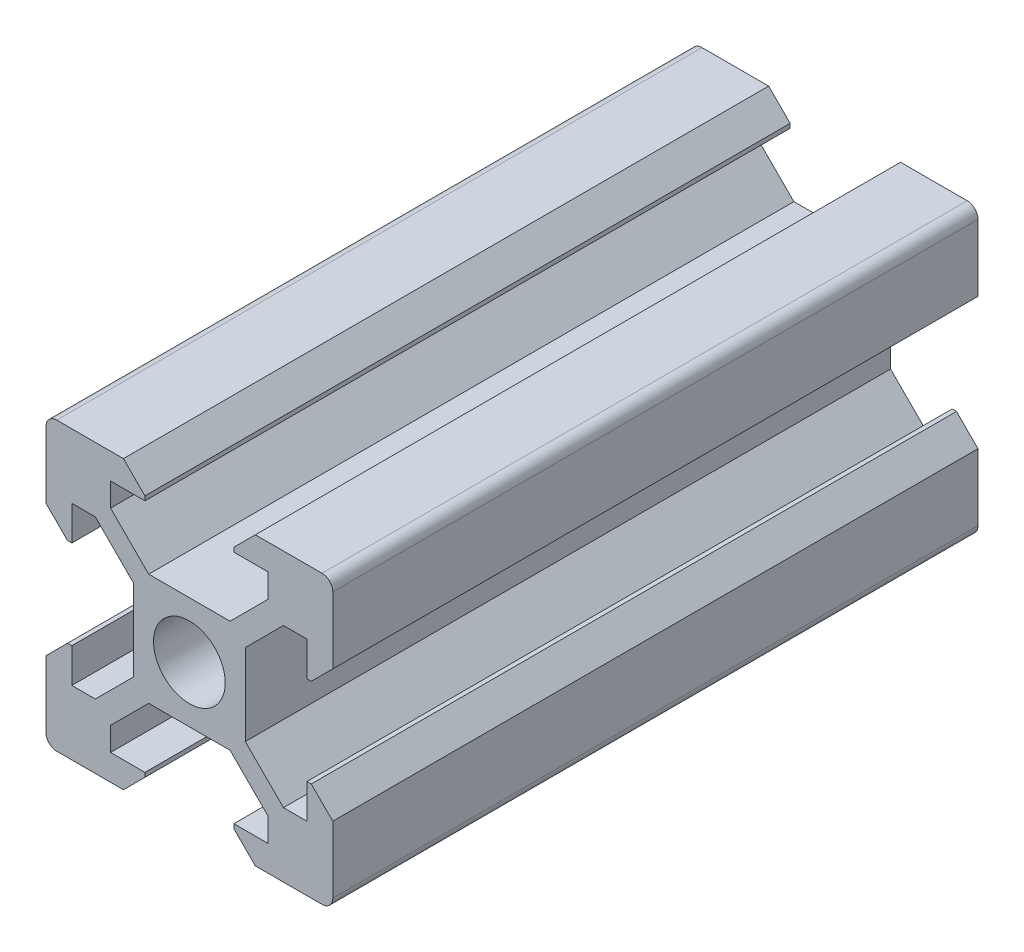
SolidWorks part; units mm, degrees
other "Markup1"
sketch "Sketch1" plane through (10, 10, 480) normal (0.5774, 0.5773, 0.5774) x (0.7071, 0, -0.7071)
ref_plane "Alzado" through (0, 0, 0) normal (0, 0, 1) x (1, 0, 0)
ref_plane "Planta" through (0, 0, 0) normal (0, 1, 0) x (1, 0, 0)
ref_plane "Vista lateral" through (0, 0, 0) normal (1, 0, 0) x (0, 0, -1)
sketch "Croquis1" plane through (0, 0, 0) normal (0, 0, 1) x (1, 0, 0)
  line L0 (-4.6, 10) -> (-3.1, 8.5)
  line L3 (-4.6, 10) -> (-9.25, 10)
  line L5 (-3.1, 8.5) -> (-3.1, 8.2)
  line L6 (-3.1, 8.2) -> (-5.5, 8.2)
  line L7 (-5.5, 8.2) -> (-5.5, 6.5607)
  line L8 (-5.5, 6.5607) -> (-2.84, 3.9007)
  line L9 (-2.84, 3.9007) -> (0, 3.9007)
  line L10 (0, 0) -> (-15.3499, 15.3499) construction
  line L11 (-3.9007, 2.84) -> (-3.9007, 0)
  line L12 (-6.5607, 5.5) -> (-3.9007, 2.84)
  line L13 (-8.2, 5.5) -> (-6.5607, 5.5)
  line L14 (-8.2, 3.1) -> (-8.2, 5.5)
  line L15 (-8.5, 3.1) -> (-8.2, 3.1)
  line L16 (-10, 4.6) -> (-10, 9.25)
  line L17 (-10, 4.6) -> (-8.5, 3.1)
  line L18 (10, 4.6) -> (8.5, 3.1)
  line L19 (10, 4.6) -> (10, 9.25)
  line L20 (8.5, 3.1) -> (8.2, 3.1)
  line L21 (8.2, 3.1) -> (8.2, 5.5)
  line L22 (8.2, 5.5) -> (6.5607, 5.5)
  line L23 (6.5607, 5.5) -> (3.9007, 2.84)
  line L24 (3.9007, 2.84) -> (3.9007, 0)
  line L25 (5.5, 6.5607) -> (2.84, 3.9007)
  line L26 (5.5, 8.2) -> (5.5, 6.5607)
  line L27 (3.1, 8.2) -> (5.5, 8.2)
  line L28 (3.1, 8.5) -> (3.1, 8.2)
  line L29 (4.6, 10) -> (9.25, 10)
  line L30 (4.6, 10) -> (3.1, 8.5)
  line L31 (2.84, 3.9007) -> (0, 3.9007)
  line L32 (4.6, -10) -> (3.1, -8.5)
  line L33 (4.6, -10) -> (9.25, -10)
  line L34 (3.1, -8.5) -> (3.1, -8.2)
  line L35 (3.1, -8.2) -> (5.5, -8.2)
  line L36 (5.5, -8.2) -> (5.5, -6.5607)
  line L37 (5.5, -6.5607) -> (2.84, -3.9007)
  line L38 (2.84, -3.9007) -> (0, -3.9007)
  line L39 (6.5607, -5.5) -> (3.9007, -2.84)
  line L40 (8.2, -5.5) -> (6.5607, -5.5)
  line L41 (8.2, -3.1) -> (8.2, -5.5)
  line L42 (8.5, -3.1) -> (8.2, -3.1)
  line L43 (10, -4.6) -> (10, -9.25)
  line L44 (10, -4.6) -> (8.5, -3.1)
  line L45 (3.9007, -2.84) -> (3.9007, 0)
  line L46 (-10, -4.6) -> (-8.5, -3.1)
  line L47 (-10, -4.6) -> (-10, -9.25)
  line L48 (-8.5, -3.1) -> (-8.2, -3.1)
  line L49 (-8.2, -3.1) -> (-8.2, -5.5)
  line L50 (-8.2, -5.5) -> (-6.5607, -5.5)
  line L51 (-6.5607, -5.5) -> (-3.9007, -2.84)
  line L52 (-3.9007, -2.84) -> (-3.9007, 0)
  line L53 (-5.5, -6.5607) -> (-2.84, -3.9007)
  line L54 (-5.5, -8.2) -> (-5.5, -6.5607)
  line L55 (-3.1, -8.2) -> (-5.5, -8.2)
  line L56 (-3.1, -8.5) -> (-3.1, -8.2)
  line L57 (-4.6, -10) -> (-9.25, -10)
  line L58 (-4.6, -10) -> (-3.1, -8.5)
  line L59 (-2.84, -3.9007) -> (0, -3.9007)
  circle A0 centre (0, 0) radius 2.5
  arc A1 (-9.25, 10) -> (-10, 9.25) centre (-9.25, 9.25) ccw
  arc A2 (10, 9.25) -> (9.25, 10) centre (9.25, 9.25) ccw
  arc A3 (9.25, -10) -> (10, -9.25) centre (9.25, -9.25) ccw
  arc A4 (-10, -9.25) -> (-9.25, -10) centre (-9.25, -9.25) ccw
  point P18 (-10, 10)
  point P37 (10, 10)
  point P55 (10, -10)
  point P73 (-10, -10)
  point P79 (0, 0)
  dimension "D1" = 5
  dimension "D5" = 0.75
  dimension "D2" = 10
  dimension "D3" = 10
  dimension "D4" = 4.6
  dimension "D6" = 5.5
  dimension "D7" = 135
  dimension "D8" = 0.75
  dimension "D9" = 225
  dimension "D10" = 2.84
  dimension "D11" = 1.8
  dimension "D12" = 3.1
  dimension "D13" = 4
extrude "Saliente-Extruir1" add sketch "Croquis1" along normal blind 480
sketch "Sketch2" plane through (0, 0, 0) normal (1, 0, 0) x (0, 0, -1)
  line L0 (-300, 40.7698) -> (-300, -37.1573) construction
  line L1 (-300, -13.485) -> (300, -13.485)
  line L2 (-300, -13.485) -> (-300, 13.485)
  line L3 (-300, 13.485) -> (300, 13.485)
  line L4 (300, -13.485) -> (300, 13.485)
  line L5 (-300, -13.485) -> (300, 13.485) construction
  line L6 (-300, 13.485) -> (300, -13.485) construction
  line L7 (-480, -2.84) -> (-480, 2.84) construction
  point P0 (0, 0)
  dimension "D1" = 180
extrude "Cut-Extrude1" cut sketch "Sketch2" against normal blind 24 and the other way blind 25 contours L2 L1 L4 L3
sketch "Sketch4" plane through (0, 0, 0) normal (1, 0, 0) x (0, 0, -1)
  line L0 (-480, 4.6) -> (-480, 9.25) construction
  line L1 (-435, 35.0285) -> (-295, 35.0285)
  line L2 (-435, 35.0285) -> (-435, -36.5767)
  line L3 (-435, -36.5767) -> (-295, -36.5767)
  line L4 (-295, 35.0285) -> (-295, -36.5767)
  dimension "D1" = 45
  dimension "D2" = 140
extrude "Cut-Extrude4" cut sketch "Sketch4" against normal blind 41 and the other way blind 21
